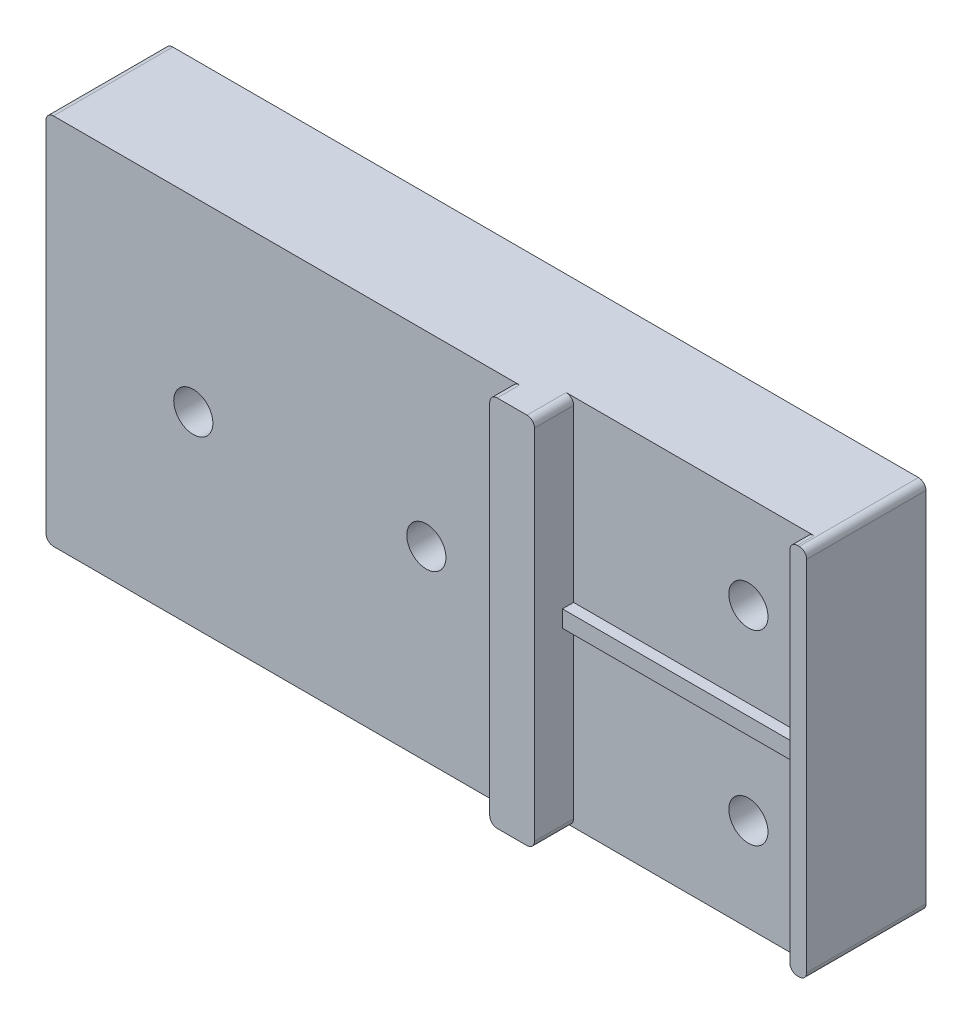
SolidWorks part; units mm, degrees
ref_plane "Front Plane" through (0, 0, 0) normal (0, 0, 1) x (1, 0, 0)
ref_plane "Top Plane" through (0, 0, 0) normal (0, 1, 0) x (1, 0, 0)
ref_plane "Right Plane" through (0, 0, 0) normal (1, 0, 0) x (0, 0, -1)
sketch "Sketch1" plane through (0, 0, 0) normal (0, -1, 0) x (1, 0, 0)
  line L19 (14, 12.8) -> (40.8, 12.8) construction
  line L20 (14, 15.2) -> (14, 12.8)
  line L21 (-40.8, 0) -> (-40.8, 12.8)
  line L22 (40.8, 0) -> (-40.8, 0)
  line L23 (40.8, 12.8) -> (40.8, 0)
  line L24 (9.2, 15.2) -> (14, 15.2)
  line L25 (9.2, 12.8) -> (9.2, 15.2)
  line L26 (-40.8, 12.8) -> (9.2, 12.8)
  line L32 (-40.8, 12.8) -> (-40.8, 31) construction
  line L33 (-40.8, 31) -> (-40.8, 43.8) construction
  line L34 (-40.8, 43.8) -> (40.8, 43.8) construction
  line L35 (40.8, 43.8) -> (40.8, 31) construction
  line L36 (14, 12.8) -> (14, 11)
  line L37 (14, 11) -> (39, 11)
  line L38 (39, 11) -> (39, 12.8)
  line L39 (39, 12.8) -> (40.8, 12.8)
  line L40 (40.8, 31) -> (39, 31) construction
  line L41 (39, 31) -> (39, 32.8) construction
  line L42 (39, 32.8) -> (14, 32.8) construction
  line L43 (14, 32.8) -> (14, 31) construction
  line L44 (14, 28.6) -> (9.2, 28.6) construction
  line L45 (9.2, 31) -> (-40.8, 31) construction
  line L46 (14, 31) -> (14, 28.6) construction
  line L47 (9.2, 31) -> (9.2, 28.6) construction
  line L48 (-45.1978, 21.9) -> (59.4667, 21.9) construction
  line L49 (51.1238, 39.4) -> (51.1238, 4.4) construction
  point P0 (0, 0)
  point P2 (-40.8, 21.9)
  point P29 (51.1238, 21.9)
  dimension "D2" = 12.8
  dimension "D3" = 50
  dimension "D4" = 4.8
  dimension "D6" = 2.4
  dimension "D7" = 18.2
  dimension "D8" = 21.8
  dimension "D9" = 1.8
  dimension "D10" = 25
  dimension "D11" = 1.8
  dimension "D12" = 11
  dimension "D13" = 35
  dimension "D14" = 6.6
  dimension "D15" = 4.4
extrude "Boss-Extrude1" add sketch "Sketch1" along normal blind 40
sketch "Sketch6" plane through (0, 0, 0) normal (0, 0, -1) x (-1, 0, 0)
  line L0 (40.8, -40) -> (40.8, 0) construction
  line L1 (-9.2, -40) -> (-9.2, 0) construction
  line L2 (-9.2, -40) -> (-9.2, 0) construction
  circle A0 centre (25, -20) radius 2.1
  circle A1 centre (0, -20) radius 2.1
  point P4 (40.8, -20)
  dimension "D1" = 4.2
  dimension "D3" = 4.2
  dimension "D2" = 34.2
  dimension "D4" = 9.2
extrude "Cut-Extrude4" cut sketch "Sketch6" against normal up to surface (12.8 mm away) up to face at (-15.8, -20, 12.8)
sketch "Sketch10" plane through (0, 0, 11) normal (0, 0, 1) x (1, 0, 0)
  line L0 (14, -20) -> (39, -20) construction
  line L1 (39, -20) -> (39, 0) construction
  line L2 (39, 0) -> (26.5, -20) construction
  line L3 (26.5, -20) -> (39, -40) construction
  line L4 (39, 0) -> (14, 0)
  line L5 (14, 0) -> (14, -40)
  line L6 (14, -40) -> (39, -40)
  line L7 (39, -40) -> (39, 0)
  line L8 (39, 0) -> (14, 0) construction
  line L9 (14, 0) -> (14, -40) construction
  line L10 (14, -40) -> (39, -40) construction
  line L11 (39, -40) -> (39, 0) construction
  circle A0 centre (32.75, -10) radius 2.1
  circle A1 centre (32.75, -30) radius 2.1
  dimension "D2" = 4.2
  dimension "D1" = 0
extrude "Cut-Extrude7" cut sketch "Sketch10" against normal up to next
sketch "Sketch11" plane through (0, 0, 0) normal (0, 0, -1) x (-1, 0, 0)
  circle A4 centre (-32.75, -10) radius 4.75
  circle A5 centre (-32.75, -30) radius 4.75
  dimension "D1" = 9.5
extrude "Cut-Extrude8" cut sketch "Sketch11" against normal blind 4.5
sketch "Sketch12" plane through (0, 0, 4.5) normal (0, 0, -1) x (-1, 0, 0)
  circle A0 centre (-32.75, -10) radius 2.1 construction
  circle A1 centre (-32.75, -30) radius 2.1 construction
  circle A2 centre (-32.75, -10) radius 2.1
  circle A3 centre (-32.75, -30) radius 2.1
extrude "Boss-Extrude2" add sketch "Sketch12" against normal blind 0.6
sketch "Sketch13" plane through (0, 0, 11) normal (0, 0, 1) x (1, 0, 0)
  line L0 (39, -40) -> (39, 0) construction
  line L1 (14, -19.1) -> (39, -19.1)
  line L2 (14, -19.1) -> (14, -20.9)
  line L3 (14, -20.9) -> (39, -20.9)
  line L4 (39, -19.1) -> (39, -20.9)
  line L5 (14, -19.1) -> (39, -20.9) construction
  line L6 (14, -20.9) -> (39, -19.1) construction
  line L7 (14, -40) -> (14, 0) construction
  line L8 (39, -40) -> (39, 0) construction
  line L9 (14, -40) -> (14, 0) construction
  point P0 (26.5, -20)
  point P9 (14, -20)
  point P10 (14, -20)
  point P11 (39, -20)
  point P12 (39, -20)
  dimension "D1" = 1.8
extrude "Boss-Extrude3" add sketch "Sketch13" along normal blind 1.2
fillet "Fillet1" radius 0.8 10 edges at (39, 0, 11.9) (39, -40, 11.9) (14, -40, 13.1) (9.2, -40, 14) (9.2, 0, 14) (14, 0, 13.1) (-40.8, 0, 6.4) (-40.8, -40, 6.4) (40.8, 0, 6.4) (40.8, -40, 6.4)
